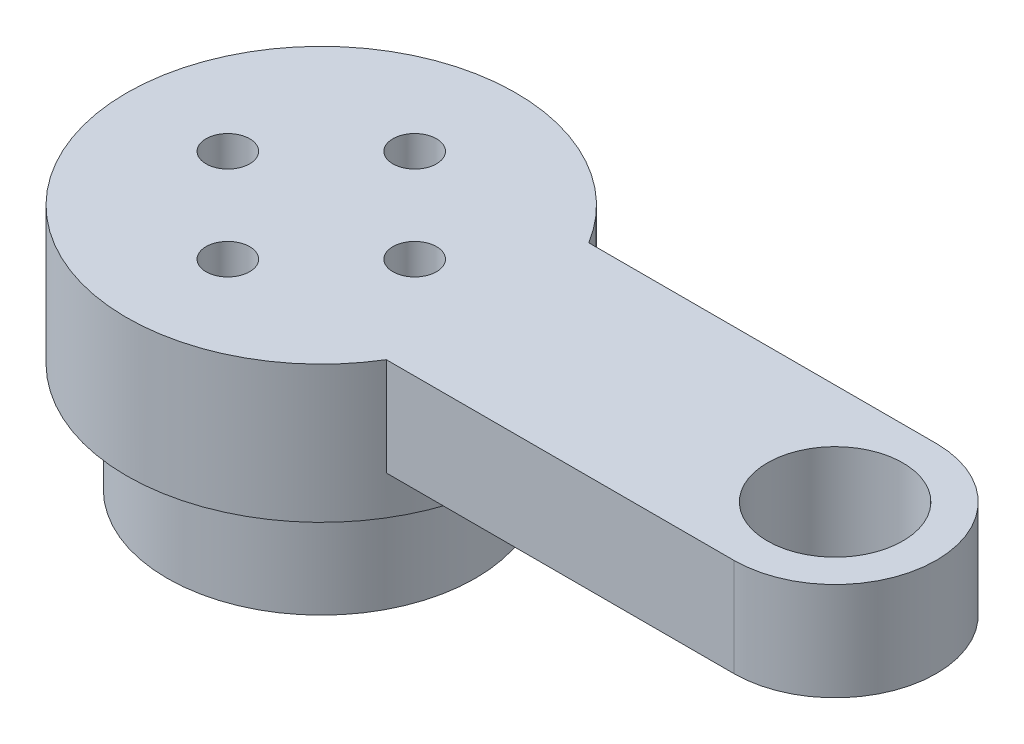
SolidWorks part; units mm, degrees
ref_plane "前视基准面" through (0, 0, 0) normal (0, 0, 1) x (1, 0, 0)
ref_plane "上视基准面" through (0, 0, 0) normal (0, 1, 0) x (1, 0, 0)
ref_plane "右视基准面" through (0, 0, 0) normal (1, 0, 0) x (0, 0, -1)
sketch "草图1" plane through (0, 0, 0) normal (0, 1, 0) x (1, 0, 0)
  line L0 (-1000, 0) -> (49000, 0) construction
  circle A0 centre (0, 0) radius 9.9
  circle A1 centre (6, 0) radius 1.4
  circle A2 centre (0, -6) radius 1.4
  circle A3 centre (-6, 0) radius 1.4
  circle A4 centre (0, 6) radius 1.4
  point P16 (0, 0)
  dimension "D1" = 19.8
  dimension "D2" = 2.8
  dimension "D3" = 6
  dimension "D4" = 4
extrude "凸台-拉伸1" add sketch "草图1" along normal blind 7
sketch "草图2" plane through (0, 7, 0) normal (0, 1, 0) x (1, 0, 0)
  circle A0 centre (0, 0) radius 12.5
  circle A1 centre (-6, 0) radius 1.4 construction
  circle A2 centre (0, -6) radius 1.4 construction
  circle A3 centre (6, 0) radius 1.4 construction
  circle A4 centre (0, 6) radius 1.4 construction
  circle A5 centre (-6, 0) radius 1.4
  circle A6 centre (0, -6) radius 1.4
  circle A7 centre (6, 0) radius 1.4
  circle A8 centre (0, 6) radius 1.4
  dimension "D1" = 25
extrude "凸台-拉伸2" add sketch "草图2" along normal blind 2.5
sketch "草图3" plane through (0, 9.5, 0) normal (0, 1, 0) x (1, 0, 0)
  line L0 (-1000, 0) -> (49000, 0) construction
  line L1 (33, -6.5) -> (10.6771, -6.5)
  line L2 (33, 6.5) -> (10.6771, 6.5)
  circle A0 centre (0, -6) radius 1.4 construction
  circle A1 centre (-6, 0) radius 1.4 construction
  circle A2 centre (0, 6) radius 1.4 construction
  circle A3 centre (6, 0) radius 1.4 construction
  circle A4 centre (0, 0) radius 12.5 construction
  circle A5 centre (0, -6) radius 1.4
  circle A6 centre (-6, 0) radius 1.4
  circle A7 centre (0, 6) radius 1.4
  circle A8 centre (6, 0) radius 1.4
  circle A9 centre (0, 0) radius 12.5
  circle A10 centre (33, 0) radius 4.35
  circle A15 centre (33, 0) radius 6.5
  point P29 (0, 0)
  dimension "D1" = 8.7
  dimension "D4" = 33
  dimension "D5" = 13
extrude "凸台-拉伸3" add sketch "草图3" along normal blind 6.3
